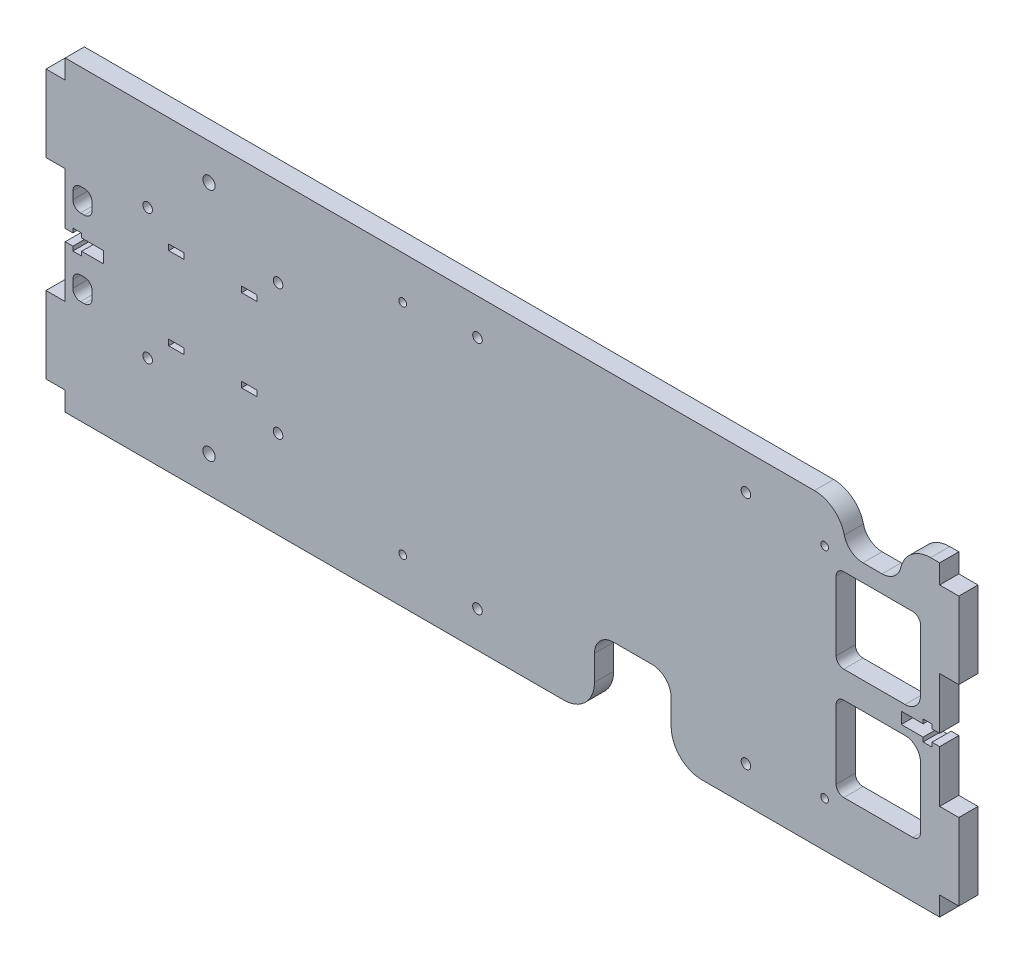
SolidWorks part; units mm, degrees
ref_plane "Plan de face" through (0, 0, 0) normal (0, 0, 1) x (1, 0, 0)
ref_plane "Plan de dessus" through (0, 0, 0) normal (0, 1, 0) x (1, 0, 0)
ref_plane "Plan de droite" through (0, 0, 0) normal (1, 0, 0) x (0, 0, -1)
sketch "Esquisse1" plane through (0, 0, 0) normal (0, 0, 1) x (1, 0, 0)
  line L0 (0, 35) -> (0, 15)
  line L1 (0, 15) -> (5, 15)
  line L2 (5, 15) -> (5, 1.5)
  line L3 (5, 1.5) -> (7, 1.5)
  line L4 (7, 1.5) -> (7, 2.6)
  line L5 (7, 2.6) -> (9.3, 2.6)
  line L6 (9.3, 2.6) -> (9.3, 1.5)
  line L7 (9.3, 1.5) -> (15, 1.5)
  line L8 (15, 1.5) -> (15, -1.5)
  line L9 (15, -1.5) -> (9.3, -1.5)
  line L10 (9.3, -1.5) -> (9.3, -2.6)
  line L11 (9.3, -2.6) -> (7, -2.6)
  line L12 (7, -2.6) -> (7, -1.5)
  line L13 (7, -1.5) -> (5, -1.5)
  line L14 (5, -1.5) -> (5, -15)
  line L15 (5, -15) -> (0, -15)
  line L16 (0, -15) -> (0, -35)
  line L17 (0, 35) -> (5, 35)
  line L18 (5, 35) -> (5, 40)
  line L19 (119, -36.5) -> (119, 67.7368) construction
  line L20 (0, 0) -> (119, 0) construction
  line L21 (238, 35) -> (238, 15)
  line L22 (238, 15) -> (233, 15)
  line L23 (233, 15) -> (233, 1.5)
  line L24 (233, 1.5) -> (231, 1.5)
  line L25 (231, 1.5) -> (231, 2.6)
  line L26 (231, 2.6) -> (228.7, 2.6)
  line L27 (228.7, 2.6) -> (228.7, 1.5)
  line L28 (228.7, 1.5) -> (223, 1.5)
  line L29 (223, 1.5) -> (223, -1.5)
  line L30 (223, -1.5) -> (228.7, -1.5)
  line L31 (228.7, -1.5) -> (228.7, -2.6)
  line L32 (228.7, -2.6) -> (231, -2.6)
  line L33 (231, -2.6) -> (231, -1.5)
  line L34 (231, -1.5) -> (233, -1.5)
  line L35 (233, -1.5) -> (233, -15)
  line L36 (233, -15) -> (238, -15)
  line L37 (238, -15) -> (238, -35)
  line L38 (5, 40) -> (233, 40)
  line L39 (233, 40) -> (233, 35)
  line L40 (233, 35) -> (238, 35)
  line L41 (238, -35) -> (233, -35)
  line L42 (233, -35) -> (233, -40)
  line L43 (233, -40) -> (5, -40)
  line L44 (5, -40) -> (5, -35)
  line L45 (5, -35) -> (0, -35)
  line L46 (32, -11.5) -> (32, -10)
  line L47 (32, 11.5) -> (36, 11.5)
  line L48 (32, 11.5) -> (32, 10)
  line L49 (32, 10) -> (36, 10)
  line L50 (36, 11.5) -> (36, 10)
  line L51 (51, 11.5) -> (55, 11.5)
  line L52 (51, 11.5) -> (51, 10)
  line L53 (51, 10) -> (55, 10)
  line L54 (55, 11.5) -> (55, 10)
  line L55 (32, -10) -> (36, -10)
  line L56 (36, -11.5) -> (36, -10)
  line L57 (32, -11.5) -> (36, -11.5)
  line L58 (51, -11.5) -> (51, -10)
  line L59 (51, -10) -> (55, -10)
  line L60 (55, -11.5) -> (55, -10)
  line L61 (51, -11.5) -> (55, -11.5)
  line L62 (239.1547, 0) -> (-3.4925, 0) construction
  line L63 (203, 28.8228) -> (93, 28.8228) construction
  line L64 (93, 28.8228) -> (93, -28.1772) construction
  line L65 (93, -28.1772) -> (203, -28.1772) construction
  line L66 (203, -28.1772) -> (203, 28.8228) construction
  line L67 (182.5, -30.615) -> (42.5, -30.615) construction
  line L68 (112.5, 30.615) -> (112.5, -30.615) construction
  circle A0 centre (203, -28.1772) radius 1
  circle A1 centre (203, 28.8228) radius 1
  circle A2 centre (93, -28.1772) radius 1
  circle A3 centre (93, 28.8228) radius 1
  circle A4 centre (112.5, -30.615) radius 1.25
  circle A5 centre (42.5, -30.615) radius 1.6
  circle A6 centre (182.5, -30.615) radius 1.25
  circle A7 centre (42.5, 30.615) radius 1.6
  circle A8 centre (182.5, 30.615) radius 1.25
  circle A9 centre (112.5, 30.615) radius 1.25
  point P31 (119, 33.5)
  point P88 (0, 0)
  point P89 (0, 0)
  point P90 (0, 0)
  point P91 (70.3263, -30.615)
  point P92 (0, 0)
  dimension "D19" = 30
  dimension "D23" = 2.5
  dimension "D2" = 3
  dimension "D3" = 5.2
  dimension "D4" = 2.3
  dimension "D5" = 5
  dimension "D6" = 2
  dimension "D7" = 10
  dimension "D8" = 30
  dimension "D9" = 238
  dimension "D10" = 20
  dimension "D11" = 20
  dimension "D12" = 80
  dimension "D13" = 5
  dimension "D14" = 57
  dimension "D15" = 110
  dimension "D16" = 4
  dimension "D17" = 1.5
  dimension "D18" = 15
  dimension "D20" = 10
  dimension "D21" = 61.23
  dimension "D22" = 70
  dimension "D24" = 6.5
extrude "Boss.-Extru.1" add sketch "Esquisse1" along normal blind 5
sketch "Sketch1" plane through (0, 0, 0) normal (0, 0, -1) x (-1, 0, 0)
  line L0 (-5, 15) -> (-5, 1.5) construction
  line L5 (-5, -35) -> (-5, -40) construction
  line L6 (-233, 40) -> (-5, 40) construction
  line L7 (-208, 40) -> (-223, 40)
  line L8 (-208, 40) -> (-208, 30)
  line L9 (-208, 30) -> (-223, 30)
  line L10 (-223, 40) -> (-223, 30)
  line L11 (-12, 13) -> (-7, 13)
  line L12 (-236.561, 0) -> (-128.3605, 0) construction
  line L18 (-163, -40.4299) -> (-143, -40.4299)
  line L19 (-163, -40.4299) -> (-163, -20.4299)
  line L20 (-163, -20.4299) -> (-143, -20.4299)
  line L21 (-143, -40.4299) -> (-143, -20.4299)
  line L22 (-233, 35) -> (-233, 40) construction
  line L23 (-12, 13) -> (-12, 7)
  line L24 (-12, 7) -> (-7, 7)
  line L25 (-7, 13) -> (-7, 7)
  line L26 (-20.3235, 0) -> (4.719, 0) construction
  line L27 (-7, -13) -> (-7, -7)
  line L28 (-12, -7) -> (-7, -7)
  line L29 (-12, -13) -> (-12, -7)
  line L30 (-12, -13) -> (-7, -13)
  line L31 (-233, 40) -> (-5, 40) construction
  line L32 (-228, 25.5) -> (-206, 25.5)
  line L33 (-228, -25.5) -> (-206, -25.5)
  line L34 (-228, -25.5) -> (-228, -3.5)
  line L35 (-228, -3.5) -> (-206, -3.5)
  line L36 (-206, -25.5) -> (-206, -3.5)
  line L37 (-228, 25.5) -> (-228, 3.5)
  line L38 (-206, 25.5) -> (-206, 3.5)
  line L39 (-228, 3.5) -> (-206, 3.5)
  line L40 (-233, -15) -> (-233, -1.5) construction
  line L41 (-51, -10.75) -> (-36, -10.75) construction
  line L42 (-60.5, 17) -> (-26.5, 17) construction
  line L43 (-60.5, 17) -> (-60.5, -17) construction
  line L44 (-60.5, -17) -> (-26.5, -17) construction
  line L45 (-26.5, 17) -> (-26.5, -17) construction
  line L46 (-51, -10) -> (-51, -11.5) construction
  line L47 (-36, -11.5) -> (-36, -10) construction
  line L48 (-43.5, -14.432) -> (-43.5, 22.5) construction
  circle A0 centre (-60.5, 17) radius 1.25
  circle A1 centre (-60.5, -17) radius 1.25
  circle A3 centre (-26.5, 17) radius 1.25
  circle A4 centre (-26.5, -17) radius 1.25
  point P24 (-5, -37.5)
  point P46 (-26.5, 0)
  point P55 (-43.5, -10.75)
  point P56 (-43.5, -17)
  dimension "D1" = 10
  dimension "D2" = 15
  dimension "D3" = 20
  dimension "D4" = 22
  dimension "D5" = 22
  dimension "D6" = 3.5
  dimension "D7" = 10
  dimension "D8" = 138
  dimension "D9" = 20
  dimension "D10" = 6
  dimension "D11" = 5
  dimension "D12" = 2
  dimension "D13" = 27
  dimension "D14" = 5
  dimension "D15" = 34
  dimension "D16" = 34
extrude "Cut-Extrude1" cut sketch "Sketch1" against normal blind 10
fillet "Fillet2" radius 5 4 edges at (223, 30, 2.5) (208, 30, 2.5) (143, -20.4299, 2.5) (163, -20.4299, 2.5)
fillet "Fillet3" radius 2 6 edges at (228, -25.5, 2.5) (206, -3.5, 2.5) (206, -25.5, 2.5) (206, 3.5, 2.5) (228, 25.5, 2.5) (206, 25.5, 2.5)
fillet "Congé1" radius 8 4 edges at (223, 40, 2.5) (208, 40, 2.5) (163, -40, 2.5) (143, -40, 2.5)
fillet "Congé2" radius 2 8 edges at (7, -13, 2.5) (12, -13, 2.5) (7, -7, 2.5) (12, -7, 2.5) (12, 7, 2.5) (7, 7, 2.5) (7, 13, 2.5) (12, 13, 2.5)
fillet "Congé3" radius 4 2 edges at (228, 3.5, 2.5) (228, -3.5, 2.5)
